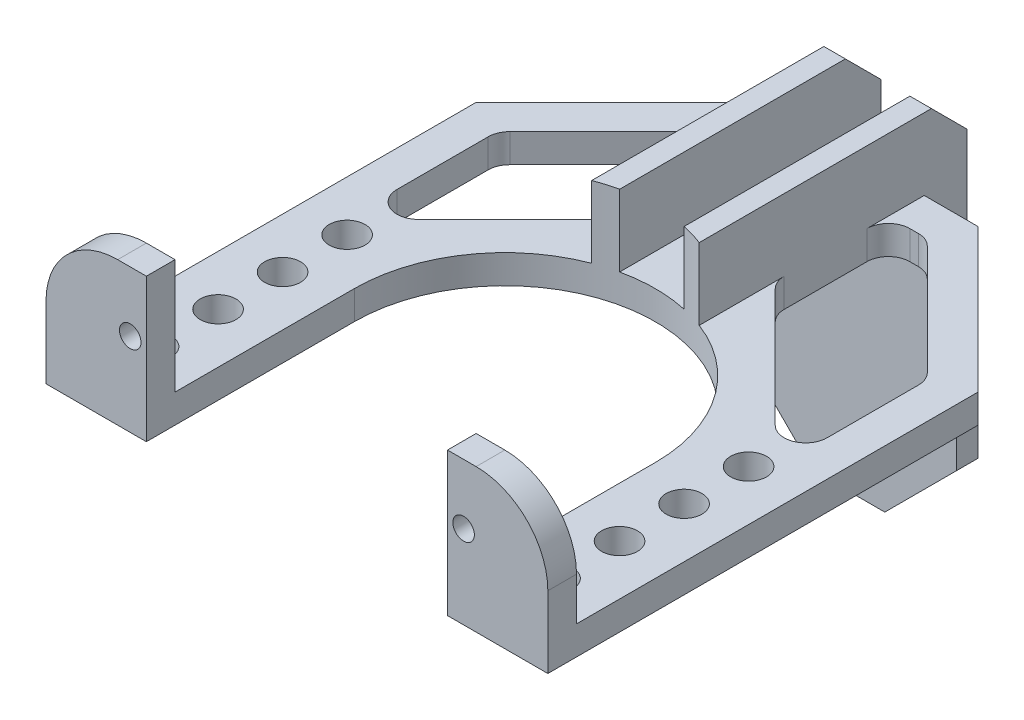
SolidWorks part; units mm, degrees
material "ABS"
ref_plane "前视基准面" through (0, 0, 0) normal (0, 0, 1) x (1, 0, 0)
ref_plane "上视基准面" through (0, 0, 0) normal (0, 1, 0) x (1, 0, 0)
ref_plane "右视基准面" through (0, 0, 0) normal (1, 0, 0) x (0, 0, -1)
sketch "草图1" plane through (0, 0, 0) normal (0, 1, 0) x (1, 0, 0)
  line L1 (0, 0) -> (70, 0)
  line L2 (0, 0) -> (0, 80)
  line L3 (0, 80) -> (70, 80)
  line L4 (70, 0) -> (70, 80)
  dimension "D1" = 70
  dimension "D2" = 80
extrude "凸台-拉伸1" add sketch "草图1" along normal blind 4
sketch "草图2" plane through (0, 4, 0) normal (0, 1, 0) x (1, 0, 0)
  line L0 (35, 0) -> (35, 80) construction
  line L1 (0, 0) -> (70, 0) construction
  line L2 (70, 80) -> (0, 80) construction
  line L3 (70, 0) -> (70, 80) construction
  line L4 (0, 0) -> (70, 0)
  line L5 (0, 0) -> (0, 4)
  line L6 (0, 4) -> (70, 4)
  line L7 (70, 0) -> (70, 4)
  dimension "D1" = 4
extrude "凸台-拉伸2" add sketch "草图2" along normal blind 16
sketch "草图4" plane through (0, 20, 0) normal (0, 1, 0) x (1, 0, 0)
  line L0 (35, 0) -> (35, 80) construction
  line L1 (0, 0) -> (70, 0) construction
  line L2 (70, 80) -> (0, 80) construction
  line L3 (14, 29) -> (14, 0)
  line L4 (14, 0) -> (56, 0)
  line L5 (56, 29) -> (56, 0)
  arc A0 (56, 29) -> (14, 29) centre (35, 29) ccw
  dimension "D2" = 42
  dimension "D1" = 29
extrude "切除-拉伸1" cut sketch "草图4" against normal through all
chamfer "倒角1" distance 20 angle 45 2 edges at (70, 2, -80) (0, 2, -80)
sketch "草图8" plane through (0, 0, 0) normal (0, -1, 0) x (1, 0, 0)
  line L1 (20, -80) -> (50, -80)
  line L2 (20, -80) -> (20, -77)
  line L3 (20, -77) -> (50, -77)
  line L4 (50, -80) -> (50, -77)
  dimension "D1" = 30
  dimension "D2" = 3
extrude "凸台-拉伸4" add sketch "草图8" along normal blind 34
sketch "草图10" plane through (0, 4, 0) normal (0, 1, 0) x (1, 0, 0)
  line L0 (35, 80) -> (35, 50) construction
  line L1 (50, 80) -> (20, 80) construction
  line L4 (42.5, 48.615) -> (42.5, 80)
  line L5 (42.5, 80) -> (27.5, 80)
  line L6 (27.5, 48.615) -> (27.5, 80)
  line L7 (43.2602, 47.1031) -> (27.5, 80) construction
  line L8 (42.5, 80) -> (26.7398, 47.1031) construction
  arc A0 (56, 29) -> (14, 29) centre (35, 29) ccw construction
  arc A1 (42.5, 48.615) -> (27.5, 48.615) centre (35, 29) ccw
  point P7 (35, 64.3449)
  dimension "D1" = 15
extrude "凸台-拉伸6" add sketch "草图10" along normal blind 10
sketch "草图11" plane through (0, 14, 0) normal (0, 1, 0) x (1, 0, 0)
  line L0 (35, 80) -> (35, 0) construction
  line L1 (42.5, 80) -> (27.5, 80) construction
  line L3 (39.5, 42.7566) -> (30.5, 42.7566)
  line L4 (39.5, 42.7566) -> (39.5, 80)
  line L5 (39.5, 80) -> (30.5, 80)
  line L6 (30.5, 42.7566) -> (30.5, 80)
  line L7 (39.5, 42.7566) -> (30.5, 80) construction
  line L8 (39.5, 80) -> (30.5, 42.7566) construction
  point P4 (35, 61.3783)
  dimension "D1" = 9
extrude "切除-拉伸2" cut sketch "草图11" against normal blind 10
chamfer "倒角2" distance 3 angle 45 1 edges at (35, 4, -80)
sketch "草图12" plane through (0, 0, -80) normal (0, 0, -1) x (-1, 0, 0)
  line L0 (-20, -34) -> (-50, -34) construction
  line L1 (-42.5, 14) -> (-39.5, 14)
  line L2 (-42.5, 14) -> (-42.5, -34)
  line L3 (-42.5, -34) -> (-39.5, -34)
  line L4 (-39.5, 14) -> (-39.5, -34)
  line L5 (-35, 4) -> (-35, -34) construction
  line L6 (-39.5, 4) -> (-30.5, 4) construction
  line L7 (-27.5, -34) -> (-30.5, -34)
  line L8 (-27.5, 14) -> (-30.5, 14)
  line L9 (-27.5, 14) -> (-27.5, -34)
  line L10 (-30.5, 14) -> (-30.5, -34)
  dimension "D1" = 3
extrude "凸台-拉伸7" add sketch "草图12" along normal blind 6
chamfer "倒角3" distance 5 angle 45 2 edges at (41, 14, -86) (29, 14, -86)
sketch "草图13" plane through (0, 0, -80) normal (0, 0, -1) x (-1, 0, 0)
  line L0 (-42.5, -34) -> (-39.5, -34) construction
  line L1 (-39.5, -34) -> (-30.5, -34)
  line L2 (-39.5, -34) -> (-39.5, -31)
  line L3 (-39.5, -31) -> (-30.5, -31)
  line L4 (-30.5, -34) -> (-30.5, -31)
  line L5 (-39.5, -34) -> (-39.5, 1) construction
  line L6 (-30.5, 1) -> (-30.5, -34) construction
  dimension "D1" = 3
extrude "凸台-拉伸8" add sketch "草图13" along normal blind 6
chamfer "倒角4" distance 10 angle 45 2 edges at (50, -34, -78.5) (20, -34, -78.5)
sketch "草图14" plane through (0, 4, 0) normal (0, 1, 0) x (1, 0, 0)
  line L0 (35, 50) -> (35, 86) construction
  line L1 (30.5, 86) -> (39.5, 86) construction
  line L2 (22.0711, 75) -> (5, 57.9289)
  line L3 (27.5, 80) -> (27.5, 48.615) construction
  line L4 (5, 57.9289) -> (5, 36.7157)
  line L5 (20, 80) -> (0, 60) construction
  line L6 (0, 60) -> (0, 4) construction
  line L7 (27.5, 81) -> (27.5, 48.615) construction
  line L8 (22.0711, 75) -> (27.5, 75)
  line L9 (27.5, 80) -> (20, 80) construction
  line L10 (27.5, 75) -> (27.5, 59.2157)
  line L11 (27.5, 59.2157) -> (5, 36.7157)
  line L12 (47.9289, 75) -> (42.5, 75)
  line L13 (42.5, 75) -> (42.5, 59.2157)
  line L14 (42.5, 59.2157) -> (65, 36.7157)
  line L15 (65, 57.9289) -> (65, 36.7157)
  line L16 (47.9289, 75) -> (65, 57.9289)
  arc A0 (39.5, 49.5122) -> (30.5, 49.5122) centre (35, 29) ccw construction
  dimension "D1" = 5
  dimension "D2" = 5
  dimension "D3" = 5
  dimension "D4" = 15
extrude "切除-拉伸3" cut sketch "草图14" against normal blind 4
fillet "圆角3" radius 3 10 edges at (65, 2, -57.9289) (65, 2, -36.7157) (42.5, 2, -59.2157) (42.5, 2, -75) (47.9289, 2, -75) (27.5, 2, -59.2157) (22.0711, 2, -75) (27.5, 2, -75) (5, 2, -57.9289) (5, 2, -36.7157)
sketch "草图15" plane through (0, 4, 0) normal (0, 1, 0) x (1, 0, 0)
  line L0 (7, 4) -> (7, 41.1867) construction
  line L1 (14, 4) -> (0, 4) construction
  line L2 (35, 50) -> (35, 0) construction
  arc A1 (39.5, 49.5122) -> (30.5, 49.5122) centre (35, 29) ccw construction
  circle A2 centre (7, 8) radius 2.5
  circle A3 centre (7, 17) radius 2.5
  circle A4 centre (7, 26) radius 2.5
  circle A5 centre (7, 35) radius 2.5
  circle A6 centre (63, 35) radius 2.5
  circle A7 centre (63, 26) radius 2.5
  circle A8 centre (63, 17) radius 2.5
  circle A9 centre (63, 8) radius 2.5
  dimension "D1" = 5
  dimension "D2" = 4
extrude "切除-拉伸4" cut sketch "草图15" against normal blind 4
fillet "圆角4" radius 10 2 edges at (70, 20, -2) (0, 20, -2)
extrude "切除-拉伸5" cut sketch "草图16" against normal blind 4
sketch "草图16" plane through (-162.9567, 61.9239, -4) normal (0, 0, -1) x (-0.1274, 0.9919, 0)
  circle A3 centre (-72.1513, 166.8744) radius 1.5
  circle A5 centre (-78.0753, 212.9955) radius 1.5
